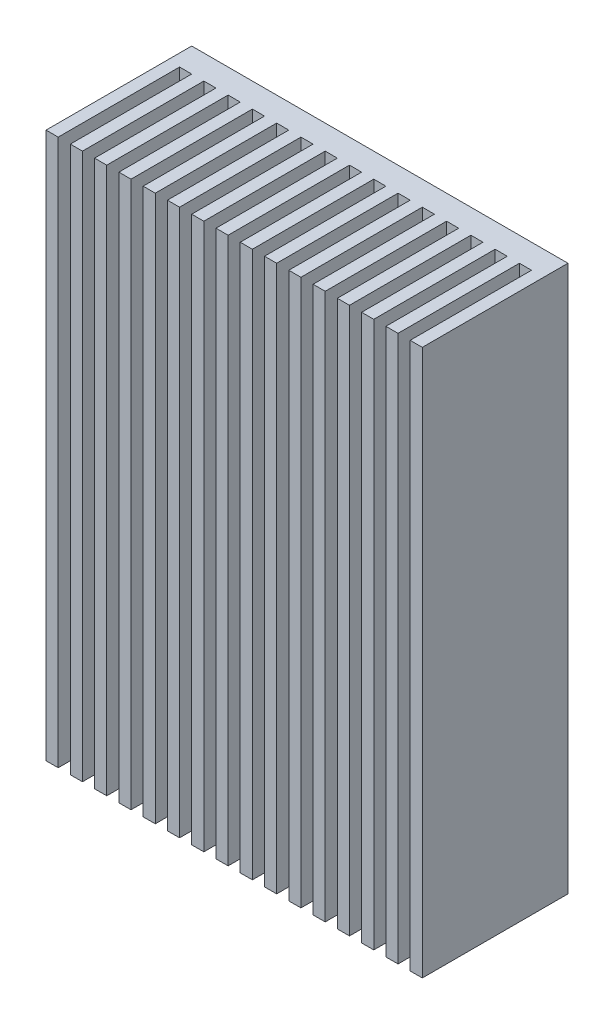
SolidWorks part; units mm, degrees
ref_plane "Front Plane" through (0, 0, 0) normal (1, 0, 0) x (0, 1, 0)
ref_plane "Top Plane" through (0, 0, 0) normal (0, 0, 1) x (0, 1, 0)
ref_plane "Right Plane" through (0, 0, 0) normal (0, 1, 0) x (-1, 0, 0)
sketch "Sketch1" plane through (0, 0, 0) normal (0, 1, 0) x (-1, 0, 0)
  line L0 (0, 2) -> (31, 2)
  line L1 (0, 0) -> (31, 0)
  line L2 (0, 0) -> (0, 12)
  line L3 (0, 12) -> (31, 12)
  line L4 (31, 0) -> (31, 12)
  line L5 (1, 2) -> (1, 12)
  line L6 (2, 2) -> (2, 12)
  line L7 (3, 2) -> (3, 12)
  line L8 (4, 2) -> (4, 12)
  line L9 (5, 2) -> (5, 12)
  line L10 (6, 2) -> (6, 12)
  line L11 (7, 2) -> (7, 12)
  line L12 (8, 2) -> (8, 12)
  line L13 (9, 2) -> (9, 12)
  line L14 (10, 2) -> (10, 12)
  line L15 (11, 2) -> (11, 12)
  line L16 (12, 2) -> (12, 12)
  line L17 (13, 2) -> (13, 12)
  line L18 (14, 2) -> (14, 12)
  line L19 (15, 2) -> (15, 12)
  line L20 (16, 2) -> (16, 12)
  line L21 (17, 2) -> (17, 12)
  line L22 (18, 2) -> (18, 12)
  line L23 (19, 2) -> (19, 12)
  line L24 (20, 2) -> (20, 12)
  line L25 (21, 2) -> (21, 12)
  line L26 (22, 2) -> (22, 12)
  line L27 (23, 2) -> (23, 12)
  line L28 (24, 2) -> (24, 12)
  line L29 (25, 2) -> (25, 12)
  line L30 (26, 2) -> (26, 12)
  line L31 (27, 2) -> (27, 12)
  line L32 (28, 2) -> (28, 12)
  line L33 (29, 2) -> (29, 12)
  line L34 (30, 2) -> (30, 12)
  dimension "D1" = 12
  dimension "D2" = 31
  dimension "D3" = 2
  dimension "D4" = 1
  dimension "D6" = 1
  dimension "D7" = 1
  dimension "D5" = 29
extrude "Boss-Extrude1" add sketch "Sketch1" along normal blind 45 contours L0 L5 L3 L2 | L1 L4 L0 L2 | L0 L7 L3 L6 | L0 L9 L3 L8 | L0 L11 L3 L10 | L0 L13 L3 L12 | L0 L15 L3 L14 | L0 L17 L3 L16 | L0 L19 L3 L18 | L0 L21 L3 L20 | L0 L23 L3 L22 | L0 L25 L3 L24 | L0 L27 L3 L26 | L0 L29 L3 L28 | L0 L31 L3 L30 | L0 L33 L3 L32 | L34 L0 L4 L3
